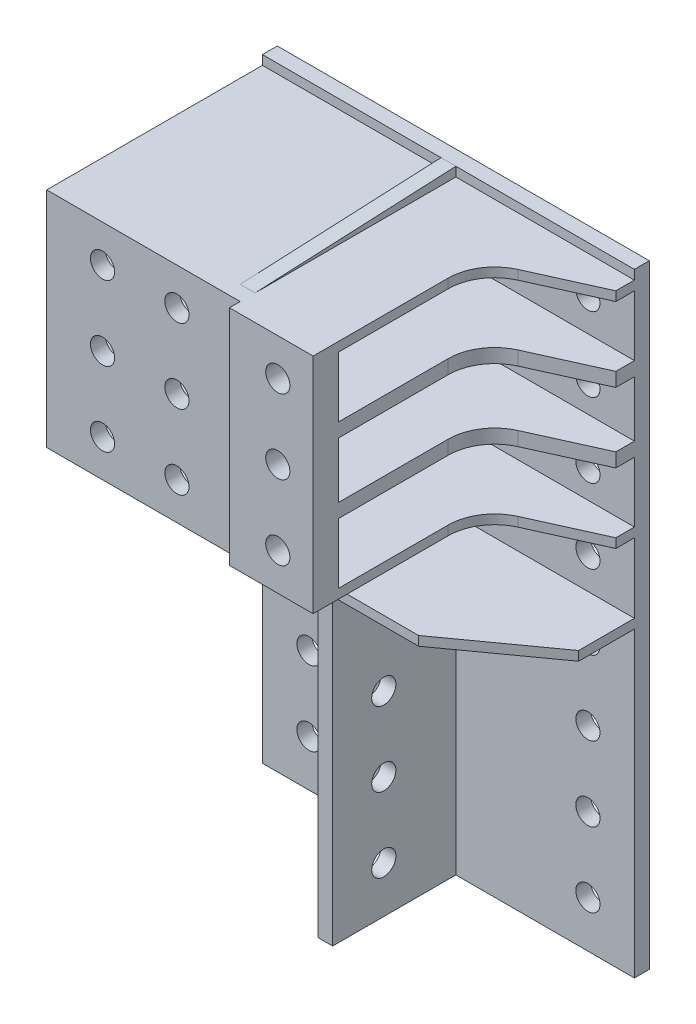
SolidWorks part; units mm, degrees
ref_plane "前视基准面" through (0, 0, 0) normal (0, 0, 1) x (1, 0, 0)
ref_plane "上视基准面" through (0, 0, 0) normal (0, 1, 0) x (1, 0, 0)
ref_plane "右视基准面" through (0, 0, 0) normal (1, 0, 0) x (0, 0, -1)
sketch "草图1" plane through (0, 0, 0) normal (0, 0, 1) x (1, 0, 0)
  line L1 (0, 0) -> (400, 0)
  line L2 (0, 0) -> (0, 660)
  line L3 (0, 660) -> (400, 660)
  line L4 (400, 0) -> (400, 660)
  dimension "D1" = 400
  dimension "D2" = 660
extrude "凸台-拉伸1" add sketch "草图1" along normal blind 16
sketch "草图2" plane through (0, 0, 16) normal (0, 0, 1) x (1, 0, 0)
  line L0 (0, 660) -> (0, 0) construction
  line L1 (400, 660) -> (0, 660) construction
  circle A0 centre (50, 610) radius 13
  dimension "D1" = 26
  dimension "D2" = 50
  dimension "D3" = 50
extrude "切除-拉伸1" cut sketch "草图2" against normal through all
pattern_linear "阵列(线性)1" count 2 spacing 300 along (1, 0, 0) count 8 spacing 80 along (0, -1, 0) of "切除-拉伸1"
sketch "草图3" plane through (0, 0, 16) normal (0, 0, 1) x (1, 0, 0)
  line L0 (200, -340) -> (200, 49660) construction
  line L1 (400, 660) -> (0, 660) construction
  line L2 (0, 0) -> (400, 0) construction
  line L3 (192, 660) -> (208, 660)
  line L4 (192, 660) -> (192, 0)
  line L5 (192, 0) -> (208, 0)
  line L6 (208, 660) -> (208, 0)
  point P5 (200, 660)
  dimension "D1" = 16
extrude "凸台-拉伸2" add sketch "草图3" along normal blind 216
sketch "草图4" plane through (208, 0, 0) normal (1, 0, 0) x (0, 0, -1)
  line L0 (-232, 660) -> (-232, 650)
  line L1 (-232, 0) -> (-232, 660) construction
  line L2 (-232, 650) -> (-16, 660)
  line L3 (-16, 660) -> (-232, 660)
  line L4 (-232, 410) -> (-198.5, 410)
  line L5 (-148.5, 360) -> (-148.5, 0)
  line L6 (-232, 0) -> (-16, 0) construction
  line L7 (-16, 0) -> (-16, 660) construction
  line L8 (-232, 410) -> (-232, 0)
  line L9 (-232, 0) -> (-148.5, 0)
  line L10 (-93.5, -837.4401) -> (-93.5, 49162.5599) construction
  arc A0 (-198.5, 410) -> (-148.5, 360) centre (-198.5, 360) cw
  circle A1 centre (-93.5, 50) radius 13
  circle A2 centre (-93.5, 130) radius 13
  circle A3 centre (-93.5, 210) radius 13
  dimension "D3" = 50
  dimension "D6" = 26
  dimension "D1" = 10
  dimension "D2" = 240
  dimension "D4" = 132.5
  dimension "D5" = 138.5
  dimension "D7" = 50
  dimension "D8" = 80
  dimension "D9" = 80
extrude "切除-拉伸2" cut sketch "草图4" against normal through all
sketch "草图5" plane through (0, 0, 16) normal (0, 0, 1) x (1, 0, 0)
  line L0 (208, 410) -> (208, 650) construction
  line L1 (208, 650) -> (400, 650)
  line L2 (208, 650) -> (208, 640)
  line L3 (208, 640) -> (400, 640)
  line L4 (400, 650) -> (400, 640)
  line L5 (400, 0) -> (400, 660) construction
  line L6 (0, 660) -> (0, 0) construction
  line L7 (0, 650) -> (192, 650)
  line L8 (0, 650) -> (0, 640)
  line L9 (0, 640) -> (192, 640)
  line L10 (192, 650) -> (192, 640)
  line L11 (192, 660) -> (192, 0) construction
  line L12 (400, 660) -> (208, 660) construction
  dimension "D1" = 10
  dimension "D2" = 10
extrude "凸台-拉伸3" add sketch "草图5" along normal blind 216
sketch "草图6" plane through (0, 640, 0) normal (0, -1, 0) x (1, 0, 0)
  line L0 (298, 232) -> (298, 114.3004)
  line L1 (208, 232) -> (400, 232) construction
  line L2 (327.4446, 68.7211) -> (400, 36)
  line L3 (400, 232) -> (400, 16) construction
  line L4 (400, 36) -> (400, 232)
  line L5 (400, 232) -> (298, 232)
  line L6 (208, 198.5) -> (208, 232) construction
  line L7 (208, 16) -> (400, 16) construction
  arc A0 (327.4446, 68.7211) -> (298, 114.3004) centre (348, 114.3004) cw
  point P15 (298, 82)
  dimension "D4" = 50
  dimension "D1" = 90
  dimension "D2" = 66
  dimension "D3" = 20
extrude "切除-拉伸3" cut sketch "草图6" against normal through all
pattern_linear "阵列(线性)2" count 2 spacing 75 along (0, -1, 0) of "凸台-拉伸3", "切除-拉伸3"
pattern_linear "阵列(线性)3" count 2 spacing 80 along (0, -1, 0) of "阵列(线性)2", "凸台-拉伸3"
pattern_linear "阵列(线性)4" count 2 spacing 75 along (0, -1, 0) of "阵列(线性)3", "凸台-拉伸3", "阵列(线性)2"
sketch "草图7" plane through (0, 0, 16) normal (0, 0, 1) x (1, 0, 0)
  line L0 (0, 410) -> (0, 0) construction
  line L1 (0, 335) -> (400, 335)
  line L2 (0, 335) -> (0, 325)
  line L3 (0, 325) -> (400, 325)
  line L4 (400, 335) -> (400, 325)
  line L5 (400, 0) -> (400, 410) construction
  line L6 (298, 410) -> (0, 410) construction
  dimension "D1" = 10
  dimension "D2" = 85
extrude "凸台-拉伸4" add sketch "草图7" along normal blind 132
sketch "草图8" plane through (0, 325, 0) normal (0, -1, 0) x (-1, 0, 0)
  line L0 (-400, -148) -> (-300, -148)
  line L1 (-208, -148) -> (-400, -148) construction
  line L2 (-300, -148) -> (-400, -76)
  line L3 (-400, -148) -> (-400, -16) construction
  line L4 (-400, -76) -> (-400, -148)
  line L5 (0, -148) -> (-100, -148)
  line L6 (0, -148) -> (-192, -148) construction
  line L7 (-100, -148) -> (0, -76)
  line L8 (0, -148) -> (0, -16) construction
  line L9 (0, -76) -> (0, -148)
  line L10 (-208, -16) -> (-400, -16) construction
  dimension "D1" = 60
  dimension "D2" = 100
extrude "切除-拉伸4" cut sketch "草图8" against normal blind 10
sketch "草图9" plane through (0, 0, 232) normal (0, 0, 1) x (1, 0, 0)
  line L1 (0, 650) -> (298, 650)
  line L2 (0, 650) -> (0, 410)
  line L3 (0, 410) -> (298, 410)
  line L4 (298, 650) -> (298, 410)
  line L9 (192, 650) -> (0, 650) construction
  line L10 (298, 410) -> (0, 410) construction
  line L11 (298, 500) -> (298, 485) construction
  line L12 (0, 575) -> (0, 560) construction
extrude "凸台-拉伸5" add sketch "草图9" along normal blind 16
sketch "草图10" plane through (0, 0, 232) normal (0, 0, -1) x (-1, 0, 0)
  line L0 (-200, -640) -> (-200, 49360) construction
  line L1 (-192, 360) -> (-208, 360) construction
  line L2 (-1298, 530) -> (48702, 530) construction
  line L3 (-298, 410) -> (-298, 650) construction
  circle A2 centre (-140, 450) radius 13
  point P7 (-298, 530)
  point P17 (-200, 360)
  dimension "D1" = 26
  dimension "D2" = 60
  dimension "D3" = 80
extrude "切除-拉伸5" cut sketch "草图10" against normal through all
pattern_linear "阵列(线性)6" count 3 spacing 80 along (0, 1, 0) of "切除-拉伸5"
pattern_linear "阵列(线性)7" count 2 spacing 120 along (1, 0, 0) of "阵列(线性)6", "切除-拉伸5"
pattern_linear "阵列(线性)8" count 2 spacing 80 along (-1, 0, 0) of "切除-拉伸5", "阵列(线性)6"
sketch "草图11" plane through (0, 0, 248) normal (0, 0, 1) x (1, 0, 0)
  line L0 (298, 650) -> (0, 650) construction
  line L1 (298, 410) -> (208, 410)
  line L2 (298, 410) -> (298, 650)
  line L3 (298, 650) -> (208, 650)
  line L4 (208, 410) -> (208, 650)
  line L5 (208, 360) -> (208, 410) construction
  circle A0 centre (260, 610) radius 13
  circle A1 centre (260, 530) radius 13
  circle A2 centre (260, 450) radius 13
  circle A3 centre (260, 610) radius 13 construction
  circle A4 centre (260, 530) radius 13 construction
  circle A5 centre (260, 450) radius 13 construction
extrude "凸台-拉伸6" add sketch "草图11" along normal blind 11.5
